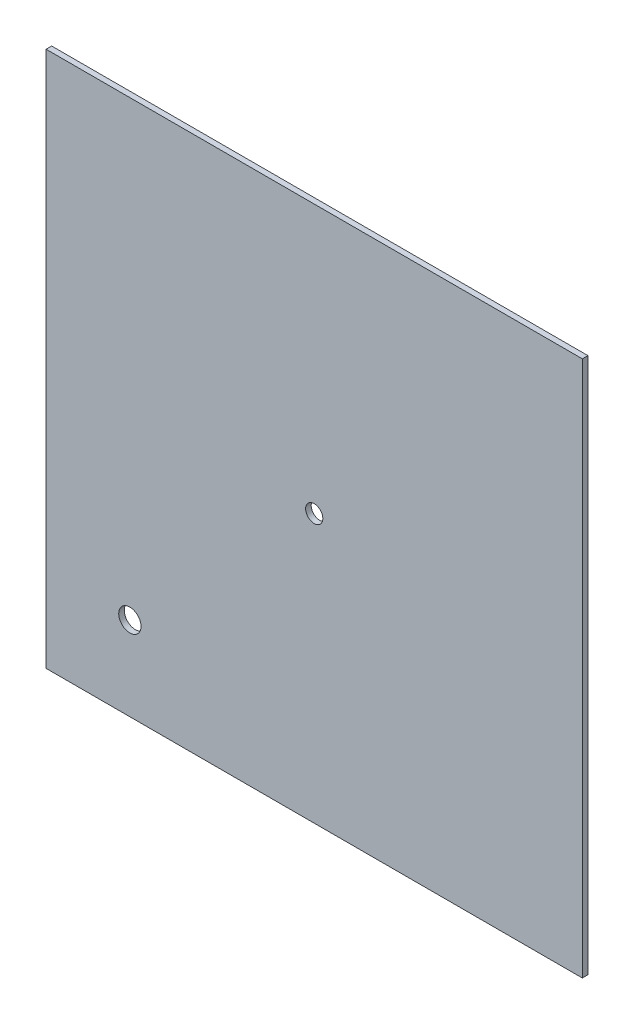
SolidWorks part; units mm, degrees
ref_plane "Front Plane" through (0, 0, 0) normal (0, 0, 1) x (1, 0, 0)
ref_plane "Top Plane" through (0, 0, 0) normal (0, 1, 0) x (1, 0, 0)
ref_plane "Right Plane" through (0, 0, 0) normal (1, 0, 0) x (0, 0, -1)
sketch "Sketch1" plane through (0, 0, 0) normal (0, 0, 1) x (1, 0, 0)
  line L1 (-152.4, -152.4) -> (152.4, -152.4)
  line L2 (-152.4, -152.4) -> (-152.4, 152.4)
  line L3 (-152.4, 152.4) -> (152.4, 152.4)
  line L4 (152.4, -152.4) -> (152.4, 152.4)
  line L5 (-152.4, -152.4) -> (152.4, 152.4) construction
  line L6 (-152.4, 152.4) -> (152.4, -152.4) construction
  circle A0 centre (0, 0) radius 4.8895
  point P0 (0, 0)
  dimension "D1" = 9.779
  dimension "D2" = 304.8
  dimension "D3" = 304.8
extrude "Boss-Extrude1" add sketch "Sketch1" along normal blind 3.175
sketch "Sketch2" plane through (0, 0, 0) normal (0, 0, -1) x (-1, 0, 0)
  line L0 (155.575, -155.575) -> (155.575, 155.575) construction
  line L1 (-152.4, -155.575) -> (152.4, -155.575) construction
  circle A0 centre (104.775, -104.775) radius 6.35
  dimension "D3" = 12.7
  dimension "D1" = 50.8
  dimension "D2" = 50.8
extrude "Cut-Extrude1" cut sketch "Sketch2" against normal blind 7.62
